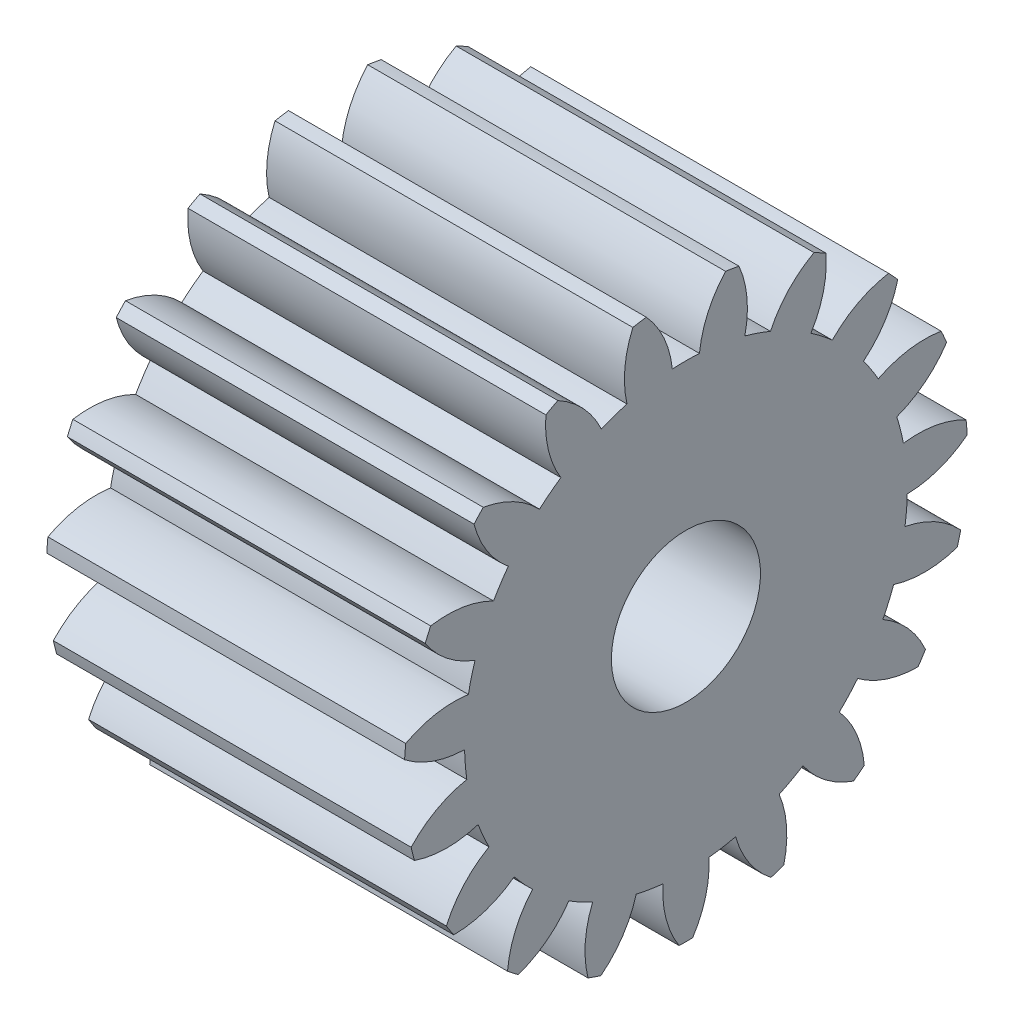
SolidWorks part; units mm, degrees
ref_plane "Plane1" through (0, 0, 0) normal (0, 0, 1) x (1, 0, 0)
ref_plane "Plane2" through (0, 0, 0) normal (0, 1, 0) x (1, 0, 0)
ref_plane "Plane3" through (0, 0, 0) normal (1, 0, 0) x (0, 0, -1)
other "Configuration Table"
sketch "HoldingSke" plane through (0, 0, 0) normal (0, 1, 0) x (1, 0, 0)
  line L0 (0, 0) -> (1.0506, -0.3617)
  line L1 (-15, 0) -> (100, 0) construction
  line L2 (0, 0) -> (-2.1039, 2.3779)
  line L3 (0, 0) -> (-11.863, 4.5341)
  line L4 (0, 0) -> (8.1655, 2.8116)
  line L5 (0, 0) -> (-46.8476, -17.4728)
  line L6 (0, 0) -> (-9.9476, -6.7116)
  line L7 (-2.1039, 2.3779) -> (8.6586, 51.2059)
  line L8 (-76.2, 54.61) -> (-75.3, 54.61)
  line L9 (-71.009, 38.7566) -> (-53.1078, 45.2721)
  line L10 (-76.2, 71.12) -> (104.1128, 71.12)
  line L11 (0, 0) -> (-12, 0)
  line L12 (-76.2, 101.6) -> (-76.166, 101.6)
  line L13 (24.9733, 27.94) -> (52.9518, 28.4284)
  line L14 (24.9733, 27.94) -> (24.9743, 27.94)
  line L15 (24.9733, 27.94) -> (100.4006, 29.5858)
  line L16 (-63.627, -0.9) -> (-12.827, -0.9)
  circle A0 centre (0, 0) radius 2.5
  circle A1 centre (0, 0) radius 7.424
  circle A2 centre (0, 0) radius 37.5
  circle A3 centre (0, 0) radius 2.5
  dimension "MHD" = 14.848
  dimension "Hub_dia" = 75
  dimension "Bore" = 5
  dimension "MBD" = 5
  dimension "Num_teeth" = 19
  dimension "Pitch" = 1.1111
  dimension "Overall_len" = 50
  dimension "Show_teeth" = 19
  dimension "Thickness" = 12
  dimension "OAL" = 50.0001
  dimension "T_dim" = 0.9
  dimension "Ap" = 20
  dimension "H" = 19.05
  dimension "Pitch_radius" = 180.3128
  dimension "Width" = 12
  dimension "Backlash" = 0.034
  dimension "Addendum_fac" = 1
  dimension "Dedendum_fac" = 1.25
  dimension "Clearance_fac" = 0.25
  dimension "Dedendum_add" = 0.001
  dimension "Module" = 0.9
sketch "BasProSke" plane through (0, 0, 0) normal (0, 1, 0) x (1, 0, 0)
  line L0 (-10, 0) -> (60, 0) construction
  line L1 (0, 0) -> (0, 9.45)
  line L2 (0, 0) -> (12, 0)
  line L3 (12, 0) -> (12, 9.45)
  line L4 (12, 9.45) -> (0, 9.45)
  dimension "Thickness" = 12
  dimension "Diameter" = 18.9
revolve "Base-Revolve" add sketch "BasProSke" angle 360 about L0
sketch "TooCutSke" plane through (0, 0, 0) normal (1, 0, 0) x (0, 0, -1)
  line L1 (0, 0) -> (0, 107) construction
  line L2 (0, 0) -> (-0.7655, 8.5157) construction
  line L3 (0, 0) -> (-2.8065, 16.8185) construction
  line L4 (-0.7655, 8.5157) -> (-1.4033, 8.4092) construction
  arc A0 (0.4542, 7.4101) -> (-0.4542, 7.4101) centre (0, 0) ccw
  arc A1 (1.3511, 9.3786) -> (-1.3511, 9.3786) centre (0, 0) ccw
  circle A2 centre (0, 0) radius 8.55 construction
  circle A3 centre (0, 0) radius 8.0344 construction
  arc A4 (-0.4542, 7.4101) -> (-1.3511, 9.3786) centre (-3.8551, 7.0491) ccw
  arc A5 (1.3511, 9.3786) -> (0.4542, 7.4101) centre (3.8551, 7.0491) ccw
  dimension "Root_dia" = 14.848
  dimension "Overcut_dia" = 18.9508
  dimension "Pitch_dia" = 17.1
  dimension "Base_dia" = 16.0687
  dimension "Flank_rad" = 3.42
  dimension "Half_ang" = 9.474
  dimension "Half_CT" = 0.6466
extrude "ToothCut" cut sketch "TooCutSke" along normal through all
fillet "Breaks" [suppressed] radius 0.018
fillet "RootFillets" [suppressed] radius 0.226
pattern_circular "TeethCuts" count 19 every 18.947 about axis through (-10, 0, 0) along (1, 0, 0) of "ToothCut", "RootFillets", "Breaks"
sketch "HubNeaOneSke" plane through (0, 0, 0) normal (-1, 0, 0) x (0, 0, 1)
  circle A0 centre (0, 0) radius 7.424
  dimension "Diameter" = 14.848
extrude "HubNearOne" [suppressed] add sketch "HubNeaOneSke" along normal blind 38.0001
sketch "HubNeaBotSke" plane through (0, 0, 0) normal (-1, 0, 0) x (0, 0, 1)
  circle A0 centre (0, 0) radius 7.424
  dimension "Diameter" = 14.848
extrude "HubNearBoth" [suppressed] add sketch "HubNeaBotSke" along normal blind 19
ref_plane "FarPln" through (12, 0, 0) normal (1, 0, 0) x (0, 0, -1)
sketch "HubFarSke" plane through (12, 0, 0) normal (1, 0, 0) x (0, 0, -1)
  circle A0 centre (0, 0) radius 7.424
  dimension "Diameter" = 14.848
extrude "HubFar" [suppressed] add sketch "HubFarSke" along normal blind 19
sketch "BorSke" plane through (0, 0, 0) normal (1, 0, 0) x (0, 0, -1)
  circle A0 centre (0, 0) radius 2.5
  dimension "Diameter" = 5
extrude "Bore" cut sketch "BorSke" along normal mid plane 100.0001
sketch "KeySke" plane through (0, 0, 0) normal (1, 0, 0) x (0, 0, -1)
  line L0 (-1, 0) -> (-1, 3.4)
  line L1 (-1, 3.4) -> (1, 3.4)
  line L2 (1, 3.4) -> (1, 0)
  line L3 (0, 0) -> (0, 34) construction
  line L4 (-1, 0) -> (1, 0)
  dimension "Offset" = 3.4
  dimension "Width" = 2
extrude "Keyway" [suppressed] cut sketch "KeySke" along normal mid plane 100.0001
pattern_circular "Keyway2" [suppressed] count 2 every 90 about axis through (-10, 0, 0) along (1, 0, 0)
sketch "Sketch1" plane through (12, 0, 0) normal (1, 0, 0) x (0, 0, -1)
  circle A0 centre (0, 0) radius 8.5
  dimension "D1" = 17
sketch "Sketch2" plane through (12, 0, 0) normal (1, 0, 0) x (0, 0, -1)
  line L0 (0, 15.4906) -> (0, -15.1972) construction
  line L1 (-16.6613, 0) -> (14.1815, 0) construction
equation "' \"Module@HoldingSke\" = 6.35"
equation "' \"Num_teeth@HoldingSke\" = 12"
equation "' \"Ap@HoldingSke\" =  20"
equation "' \"Ap@HoldingSke\" = 20"
equation "' \"Width@HoldingSke\" = 0.5 * 25.4"
equation "' \"Hub_dia@HoldingSke\"= 1 * 25.4"
equation "' \"Hub_dia@HoldingSke\" = 1 * 25.4"
equation "' \"Overall_len@HoldingSke\" = 1.0 * 25.4"
equation "' \"Bore@HoldingSke\" = 0.75 * 25.4"
equation "' \"T_dim@HoldingSke\" = 0.1 * 25.4"
equation "' \"Width@KeySke\" = 0.25 * 25.4"
equation "' \"Show_teeth@HoldingSke\" = 13"
equation "' \"Backlash@HoldingSke\" = 0.009 * 25.4"
equation "' \"Addendum_fac@HoldingSke\" = 1.0"
equation "' \"Dedendum_fac@HoldingSke\" = 1.25"
equation "' \"Dedendum_add@HoldingSke\" = 0.00005 * 25.4"
equation "' \"Clearance_fac@HoldingSke\" = 0.25"
equation "\"Pitch@HoldingSke\" = 1 / \"Module@HoldingSke\""
equation "\"Overcut_dia@TooCutSke\" = (\"Num_teeth@HoldingSke\" + 2 * \"Addendum_fac@HoldingSke\") / \"Pitch@HoldingSke\" + 0.002 * 25.4"
equation "\"Pitch_dia@TooCutSke\" = \"Num_teeth@HoldingSke\" / \"Pitch@HoldingSke\""
equation "\"Base_dia@TooCutSke\" = \"Num_teeth@HoldingSke\" / \"Pitch@HoldingSke\" * cos((\"Ap@HoldingSke\"  * 3.14159265 / 180))"
equation "\"Root_dia@TooCutSke\" = (\"Num_teeth@HoldingSke\" + 2) / \"Pitch@HoldingSke\" - 2 * (\"Addendum_fac@HoldingSke\" + \"Dedendum_fac@HoldingSke\") / \"Pitch@HoldingSke\" - \"Dedendum_add@HoldingSke\" * 2"
equation "\"Half_ang@TooCutSke\" = 180 / \"Num_teeth@HoldingSke\""
equation "\"Half_CT@TooCutSke\" = \"Num_teeth@HoldingSke\" / \"Pitch@HoldingSke\" * sin((3.14159265 / 2 / \"Num_teeth@HoldingSke\")) / 2 - 7 * \"Backlash@HoldingSke\" / 4"
equation "\"Flank_rad@TooCutSke\" = \"Num_teeth@HoldingSke\" / \"Pitch@HoldingSke\" / 5"
equation "\"Radius@RootFillets\" = \"Clearance_fac@HoldingSke\" / \"Pitch@HoldingSke\" + \"Dedendum_add@HoldingSke\""
equation "\"Break_rad@Breaks\" = 0.02 / \"Pitch@HoldingSke\""
equation "\"Thickness@HoldingSke\" = \"Width@HoldingSke\""
equation "\"OAL@HoldingSke\" = \"Thickness@HoldingSke\""
equation "\"MHD@HoldingSke\" = (\"Num_teeth@HoldingSke\" + 2) / \"Pitch@HoldingSke\" - 2 * (\"Addendum_fac@HoldingSke\" + \"Dedendum_fac@HoldingSke\")  / \"Pitch@HoldingSke\" - \"Dedendum_add@HoldingSke\" * 2"
equation "\"MBD@HoldingSke\" = (\"Num_teeth@HoldingSke\" + 2) / \"Pitch@HoldingSke\" - 2 * (\"Addendum_fac@HoldingSke\" + \"Dedendum_fac@HoldingSke\")  / \"Pitch@HoldingSke\" - \"Dedendum_add@HoldingSke\" * 2 - 0.002 * 25.4"
equation "\"MHD@HoldingSke\" = ((sgn( \"MHD@HoldingSke\" - \"Hub_dia@HoldingSke\" )-1)*( \"MHD@HoldingSke\" - \"Hub_dia@HoldingSke\" ))/-2+ \"Hub_dia@HoldingSke\""
equation "\"MBD@HoldingSke\" = ((sgn( \"MBD@HoldingSke\" - \"Bore@HoldingSke\" )-1)*( \"MBD@HoldingSke\" - \"Bore@HoldingSke\" ))/-2+ \"Bore@HoldingSke\""
equation "\"OAL@HoldingSke\" = ((sgn( \"OAL@HoldingSke\" - \"Overall_len@HoldingSke\" )+1)*( \"OAL@HoldingSke\" - \"Overall_len@HoldingSke\" ))/2 + \"Overall_len@HoldingSke\" + 0.000002 * 25.4"
equation "\"Num_teeth@TeethCuts\" = int( \"Show_teeth@HoldingSke\" ) + 1"
equation "\"Num_teeth@TeethCuts\" = ((sgn( \"Num_teeth@TeethCuts\" - \"Num_teeth@HoldingSke\" )-1)*( \"Num_teeth@TeethCuts\" - \"Num_teeth@HoldingSke\" ))/-2+ \"Num_teeth@HoldingSke\""
equation "\"Num_teeth@TeethCuts\" = ((sgn( \"Num_teeth@TeethCuts\" - 2.0)+1)*( \"Num_teeth@TeethCuts\" - 2.0))/2 +2.0"
equation "\"Angle@TeethCuts\" = 360.0 / \"Num_teeth@HoldingSke\""
equation "\"Diameter@BasProSke\" = (\"Num_teeth@HoldingSke\" + 2 * \"Addendum_fac@HoldingSke\") / \"Pitch@HoldingSke\""
equation "\"Thickness@BasProSke\"  = \"Thickness@HoldingSke\""
equation "' \"Fillet_rad@BasProSke\" =  \"Thickness@HoldingSke\" * 0.05"
equation "' \"Fillet_rad@BasProSke\" = \"Thickness@HoldingSke\" * 0.05"
equation "\"MHD@HoldingSke\" = ((sgn( \"MHD@HoldingSke\" - \"Root_dia@TooCutSke\" )-1)*( \"MHD@HoldingSke\" - \"Root_dia@TooCutSke\" ))/-2+ \"Root_dia@TooCutSke\""
equation "\"Diameter@HubNeaOneSke\" = \"MHD@HoldingSke\""
equation "\"Length@HubNearOne\" = \"OAL@HoldingSke\" - \"Thickness@BasProSke\""
equation "\"Diameter@HubNeaBotSke\" = \"MHD@HoldingSke\""
equation "\"Length@HubNearBoth\" = ( \"OAL@HoldingSke\" - \"Thickness@BasProSke\" ) / 2.0"
equation "\"Thickness@FarPln\" = \"Thickness@BasProSke\""
equation "\"Diameter@HubFarSke\" = \"MHD@HoldingSke\""
equation "\"Length@HubFar\" = ( \"OAL@HoldingSke\" - \"Thickness@BasProSke\" ) / 2.0"
equation "\"Diameter@BorSke\" = \"MBD@HoldingSke\""
equation "\"D1@Bore\" = \"OAL@HoldingSke\" * 2.0"
equation "\"D1@Keyway\" = \"OAL@HoldingSke\" * 2.0"
equation "\"Offset@KeySke\" = \"T_dim@HoldingSke\" + \"MBD@HoldingSke\" / 2.0"
